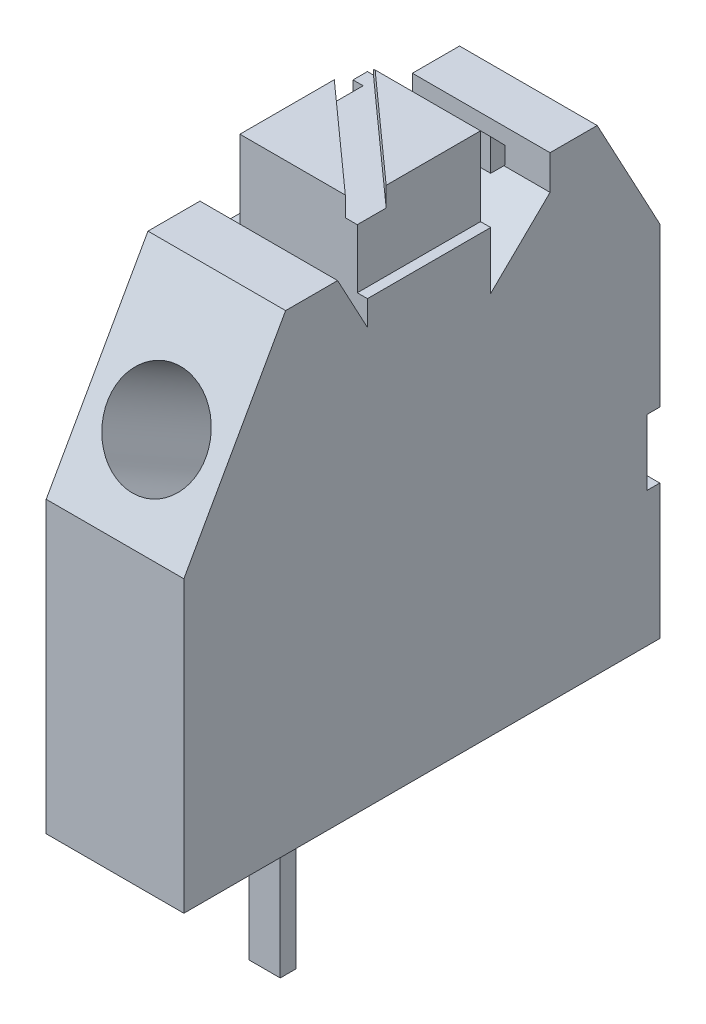
SolidWorks part; units mm, degrees
ref_plane "前视基准面" through (0, 0, 0) normal (0, 0, 1) x (1, 0, 0)
ref_plane "上视基准面" through (0, 0, 0) normal (0, 1, 0) x (1, 0, 0)
ref_plane "右视基准面" through (0, 0, 0) normal (1, 0, 0) x (0, 0, -1)
sketch "草图1" plane through (0, 0, 0) normal (0, 1, 0) x (1, 0, 0)
  line L0 (0, 11.8686) -> (0, -8.9519) construction
  line L1 (-1.75, 6.05) -> (1.75, 6.05)
  line L2 (-1.75, 6.05) -> (-1.75, -6.05)
  line L3 (-1.75, -6.05) -> (1.75, -6.05)
  line L4 (1.75, 6.05) -> (1.75, -6.05)
  line L5 (-7.6731, 0) -> (6.4167, 0) construction
  point P4 (-1.75, 0)
  dimension "D1" = 3.5
  dimension "D2" = 12.1
extrude "凸台-拉伸1" add sketch "草图1" along normal blind 13.2
sketch "草图2" plane through (-1.75, 0, 0) normal (-1, 0, 0) x (0, 0, 1)
  line L0 (-6.05, 13.2) -> (-6.05, 0) construction
  line L1 (-6.05, 5.0954) -> (-5.7193, 5.0954)
  line L2 (-6.05, 5.0954) -> (-6.05, 3.4236)
  line L3 (-6.05, 3.4236) -> (-5.7193, 3.4236)
  line L4 (-5.7193, 5.0954) -> (-5.7193, 3.4236)
  line L5 (-4.4584, 12.0922) -> (-6.05, 9.1297)
  line L6 (-4.4584, 12.0922) -> (-3.2601, 12.0922)
  line L7 (-1.7505, 9.7478) -> (-1.7505, 12.3918)
  line L8 (-6.05, 13.2) -> (6.05, 13.2) construction
  line L9 (-6.05, 9.1297) -> (-6.05, 13.2)
  line L10 (1.383, 13.2) -> (1.383, 10.5658)
  line L11 (1.383, 10.5658) -> (2.1408, 11.9771)
  line L12 (6.05, 13.2) -> (6.05, 0) construction
  line L14 (6.05, 7.3656) -> (6.05, 13.2)
  line L15 (6.05, 13.2) -> (1.383, 13.2)
  line L16 (-6.05, 13.2) -> (-1.7505, 13.2)
  line L17 (2.1408, 11.9771) -> (3.4631, 11.9771)
  line L18 (3.4631, 11.9771) -> (6.05, 7.3656)
  line L19 (-3.2601, 12.0922) -> (-3.2601, 11.2184)
  line L20 (-3.2601, 11.2184) -> (-1.7505, 9.7478)
  line L21 (-1.7505, 12.3918) -> (-2.117, 12.3918)
  line L22 (-2.117, 12.3918) -> (-2.117, 12.8245)
  line L23 (-2.117, 12.8245) -> (-1.7505, 13.2)
  dimension "D1" = 3.5
extrude "切除-拉伸1" cut sketch "草图2" against normal blind 13.2
sketch "草图8" plane through (0, 13.2, 0) normal (0, 1, 0) x (1, 0, 0)
  line L0 (0, 6.5816) -> (0, -7.1674) construction
  line L1 (1.75, -1.383) -> (-1.75, -1.383) construction
  line L2 (1.75, 1.7505) -> (1.4922, 1.7505)
  line L3 (1.75, 1.7505) -> (1.75, -1.383)
  line L4 (1.75, -1.383) -> (1.4922, -1.383)
  line L5 (1.4922, 1.7505) -> (1.4922, -1.383)
  line L6 (-1.4922, 1.7505) -> (-1.4922, -1.383)
  line L7 (-1.75, -1.383) -> (-1.4922, -1.383)
  line L8 (-1.75, 1.7505) -> (-1.75, -1.383)
  line L9 (-1.75, 1.7505) -> (-1.4922, 1.7505)
extrude "切除-拉伸4" cut sketch "草图8" against normal blind 2
sketch "草图4" plane through (0, 4.3446, 7.7447) normal (0, 0.4893, 0.8721) x (1, 0, 0)
  circle A0 centre (0, 5.6193) radius 1.25
  dimension "D1" = 2.5
extrude "切除-拉伸2" cut sketch "草图4" against normal blind 5
sketch "草图5" plane through (0, 13.2, 0) normal (0, 1, 0) x (1, 0, 0)
  line L0 (-1.75, 1.7505) -> (1.75, -1.383) construction
  line L1 (-2.2443, 1.6897) -> (-1.7022, 2.211)
  line L2 (-1.7022, 2.211) -> (2.3103, -1.3813)
  line L3 (2.3103, -1.3813) -> (1.8101, -1.9401)
  line L4 (1.8101, -1.9401) -> (-2.2443, 1.6897)
  point P4 (0, 0)
  point P7 (-1.75, 1.7505)
  dimension "D1" = 0.75
extrude "切除-拉伸3" cut sketch "草图5" against normal blind 0.5
sketch "草图6" plane through (0, 0, 0) normal (0, -1, 0) x (1, 0, 0)
  line L0 (0, 7.9025) -> (0, -7.7353) construction
  line L1 (-2.3846, 2.05) -> (1.75, 2.05) construction
  line L2 (-0.4, 2.25) -> (0.4, 2.25)
  line L3 (-0.4, 2.25) -> (-0.4, 1.85)
  line L4 (-0.4, 1.85) -> (0.4, 1.85)
  line L5 (0.4, 2.25) -> (0.4, 1.85)
  line L6 (1.75, 6.05) -> (1.75, -6.05) construction
  line L7 (-1.75, 6.05) -> (1.75, 6.05) construction
  dimension "D1" = 0.8
  dimension "D2" = 0.4
  dimension "D3" = 4
extrude "上出针" add sketch "草图6" along normal blind 4
sketch "草图7" plane through (0, 0, 0) normal (0, -1, 0) x (1, 0, 0)
  line L0 (-1.75, 6.05) -> (1.75, 6.05) construction
  line L1 (0, 3.7505) -> (0, -5.654) construction
  line L2 (-2.823, -2.95) -> (3.8393, -2.95) construction
  line L6 (-0.4, -2.75) -> (0.4, -2.75)
  line L7 (-0.4, -2.75) -> (-0.4, -3.15)
  line L8 (-0.4, -3.15) -> (0.4, -3.15)
  line L9 (0.4, -2.75) -> (0.4, -3.15)
  point P8 (0, 6.05)
  dimension "D1" = 9
  dimension "D2" = 0.4
  dimension "D3" = 0.8
extrude "下出针" [suppressed] add sketch "草图7" along normal blind 4
